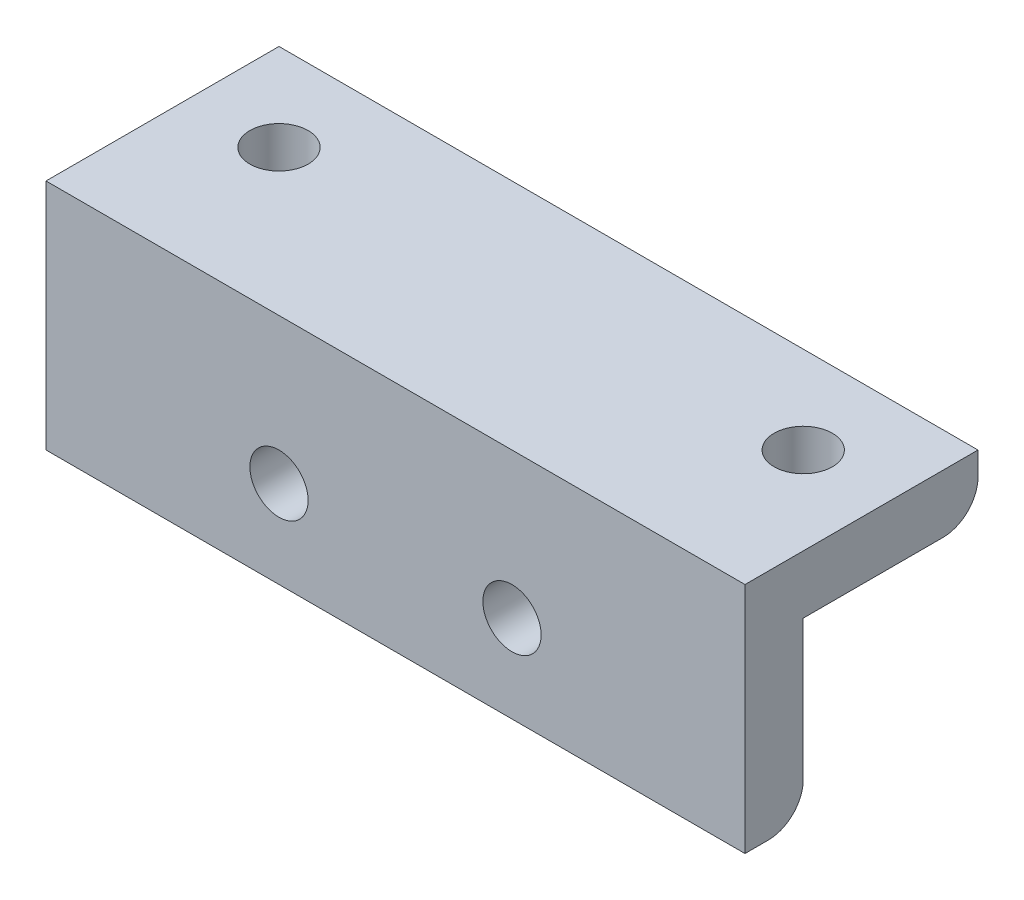
SolidWorks part; units mm, degrees
material "6061-T6 (SS)"
ref_plane "Front Plane" through (0, 0, 0) normal (0, 0, 1) x (1, 0, 0)
ref_plane "Top Plane" through (0, 0, 0) normal (0, 1, 0) x (1, 0, 0)
ref_plane "Right Plane" through (0, 0, 0) normal (1, 0, 0) x (0, 0, -1)
sketch "Sketch1" plane through (0, 0, 0) normal (1, 0, 0) x (0, 0, -1)
  line L1 (0.0269, 23.298) -> (-25.3731, 23.298)
  line L2 (0.0269, 23.298) -> (0.0269, 16.948)
  line L3 (-19.0231, -2.102) -> (-25.3731, -2.102)
  line L4 (-25.3731, 23.298) -> (-25.3731, -2.102)
  line L7 (-19.0231, 16.948) -> (0.0269, 16.948)
  line L8 (-19.0231, 16.948) -> (-19.0231, -2.102)
  point P0 (0, 0)
  point P6 (9.5873, -8.8032)
  dimension "D1" = 25.4
  dimension "D2" = 6.35
  dimension "D3" = 25.4
  dimension "D4" = 6.35
extrude "Boss-Extrude1" add sketch "Sketch1" along normal blind 76.2
fillet "Fillet2" radius 3.81 2 edges at (38.1, -2.102, 19.0231) (38.1, 16.948, -0.0269)
sketch "Sketch2" plane through (0, 23.298, 0) normal (0, 1, 0) x (1, 0, 0)
  line L0 (0, 0.0269) -> (0, -25.3731) construction
  line L1 (76.2, 0.0269) -> (76.2, -25.3731) construction
  line L2 (76.2, 0.0269) -> (0, 0.0269) construction
  circle A0 centre (9.525, -9.4981) radius 3.175
  circle A1 centre (66.675, -9.4981) radius 3.175
  dimension "D3" = 6.35
  dimension "D4" = 6.35
  dimension "D1" = 9.525
  dimension "D2" = 9.525
  dimension "D5" = 9.525
  dimension "D6" = 9.525
extrude "Cut-Extrude1" cut sketch "Sketch2" against normal blind 76.2
sketch "Sketch3" plane through (0, 0, 25.3731) normal (0, 0, 1) x (1, 0, 0)
  line L0 (0, 23.298) -> (0, -2.102) construction
  line L1 (76.2, 23.298) -> (76.2, -2.102) construction
  line L2 (76.2, -2.102) -> (0, -2.102) construction
  circle A0 centre (25.4, 7.423) radius 3.175
  circle A1 centre (50.8, 7.423) radius 3.175
  dimension "D5" = 6.35
  dimension "D6" = 6.35
  dimension "D1" = 25.4
  dimension "D2" = 25.4
  dimension "D3" = 9.525
  dimension "D4" = 9.525
extrude "Cut-Extrude2" cut sketch "Sketch3" against normal blind 76.2
